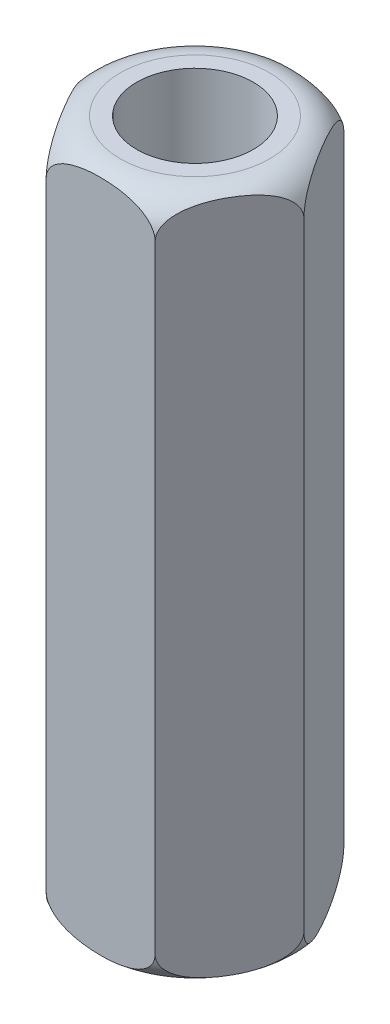
SolidWorks part; units mm, degrees
material "Brass"
ref_plane "Front Plane" through (0, 0, 0) normal (0, 0, 1) x (1, 0, 0)
ref_plane "Top Plane" through (0, 0, 0) normal (0, 1, 0) x (1, 0, 0)
ref_plane "Right Plane" through (0, 0, 0) normal (1, 0, 0) x (0, 0, -1)
sketch "Sketch1" plane through (0, 0, 0) normal (0, 1, 0) x (1, 0, 0)
  line L1 (3.1754, 0) -> (1.5877, 2.75)
  line L2 (1.5877, 2.75) -> (-1.5877, 2.75)
  line L3 (-1.5877, 2.75) -> (-3.1754, 0)
  line L4 (-3.1754, 0) -> (-1.5877, -2.75)
  line L5 (-1.5877, -2.75) -> (1.5877, -2.75)
  line L6 (1.5877, -2.75) -> (3.1754, 0)
  circle A0 centre (0, 0) radius 2.75 construction
  dimension "D1" = 5.5
extrude "Boss-Extrude1" add sketch "Sketch1" along normal blind 20
hole_wizard "M3 Clearance Hole1" positions "Sketch3" profile "Sketch2" hole size "M3" standard "ISO"
sketch "Sketch3" plane through (0, 20, 0) normal (0, 1, 0) x (-1, 0, 0)
  point P0 (0, 0)
sketch "Sketch2" plane through (0, 20, 0) normal (1, 0, 0) x (0, 0, 1)
  line L0 (0, 0) -> (0, 21.0215)
  line L1 (0, 21.0215) -> (1.7, 20)
  line L2 (1.7, 20) -> (1.7, 0)
  line L5 (1.7, 0) -> (0, 0)
  line L10 (0, 21.0215) -> (-1.7, 20) construction
  line L11 (0, -6.35) -> (0, 107.95) construction
  dimension "Hole Dia." = 3.4
  dimension "Hole Depth" = 20
  dimension "Drill Angle" = 118
sketch "Sketch4" plane through (0, 0, 0) normal (0, 0, 1) x (1, 0, 0)
  line L0 (-3.1754, 20) -> (-3.1754, 0) construction
  line L1 (-3.1754, 20) -> (-1.5877, 20) construction
  line L4 (-3.1754, 0) -> (-1.5877, 0) construction
  line L6 (-2.1754, 20) -> (-3.1754, 20)
  line L7 (-3.1754, 20) -> (-3.1754, 19)
  line L8 (-3.1754, 1) -> (-3.1754, 0)
  line L9 (-3.1754, 0) -> (-2.1754, 0)
  line L14 (0, 20) -> (0, 0) construction
  line L15 (-1.5877, 20) -> (1.5877, 20) construction
  arc A0 (-3.1754, 19) -> (-2.1754, 20) centre (-2.1754, 19) cw
  arc A2 (-3.1754, 1) -> (-2.1754, 0) centre (-2.1754, 1) ccw
  dimension "D1" = 1
revolve "Cut-Revolve1" cut sketch "Sketch4" angle 360 about L14
